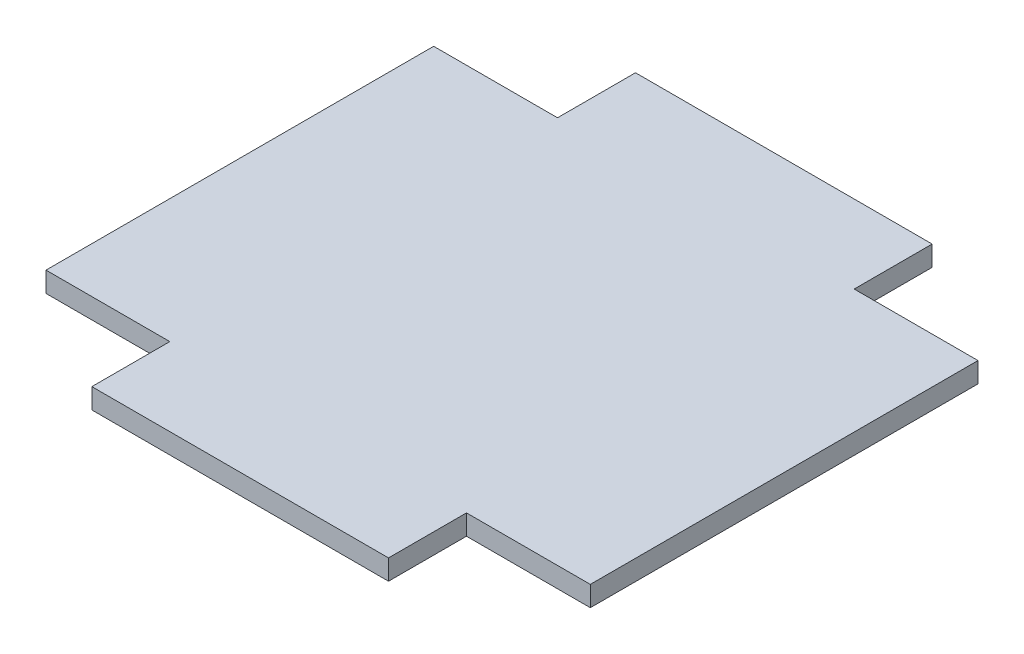
SolidWorks part; units mm, degrees
ref_plane "Front Plane" through (0, 0, 0) normal (0, 0, 1) x (1, 0, 0)
ref_plane "Top Plane" through (0, 0, 0) normal (0, 1, 0) x (1, 0, 0)
ref_plane "Right Plane" through (0, 0, 0) normal (1, 0, 0) x (0, 0, -1)
sketch "Sketch1" plane through (0, 0, 0) normal (0, 1, 0) x (1, 0, 0)
  line L1 (7.4052, -46.1643) -> (51.4052, -46.1643)
  line L3 (51.4052, 34.4657) -> (7.4052, 34.4657)
  line L9 (51.4052, -46.1643) -> (51.4052, -34.5993)
  line L14 (7.4052, -34.5993) -> (7.4052, -46.1643)
  line L15 (7.4052, -34.5993) -> (-10.9598, -34.5993)
  line L16 (-10.9598, -34.5993) -> (-10.9598, 22.9007)
  line L17 (-10.9598, 22.9007) -> (7.4052, 22.9007)
  line L18 (7.4052, 22.9007) -> (7.4052, 34.4657)
  line L19 (51.4052, 34.4657) -> (51.4052, 22.9007)
  line L20 (51.4052, 22.9007) -> (69.7702, 22.9007)
  line L21 (69.7702, 22.9007) -> (69.7702, -34.5993)
  line L22 (69.7702, -34.5993) -> (51.4052, -34.5993)
  line L23 (7.4052, 22.9007) -> (7.4052, -34.5993) construction
  line L24 (51.4052, 22.9007) -> (51.4052, -34.5993) construction
  dimension "D1" = 57.5
  dimension "D2" = 80.63
  dimension "D3" = 80.73
extrude "Boss-Extrude1" add sketch "Sketch1" along normal blind 3
